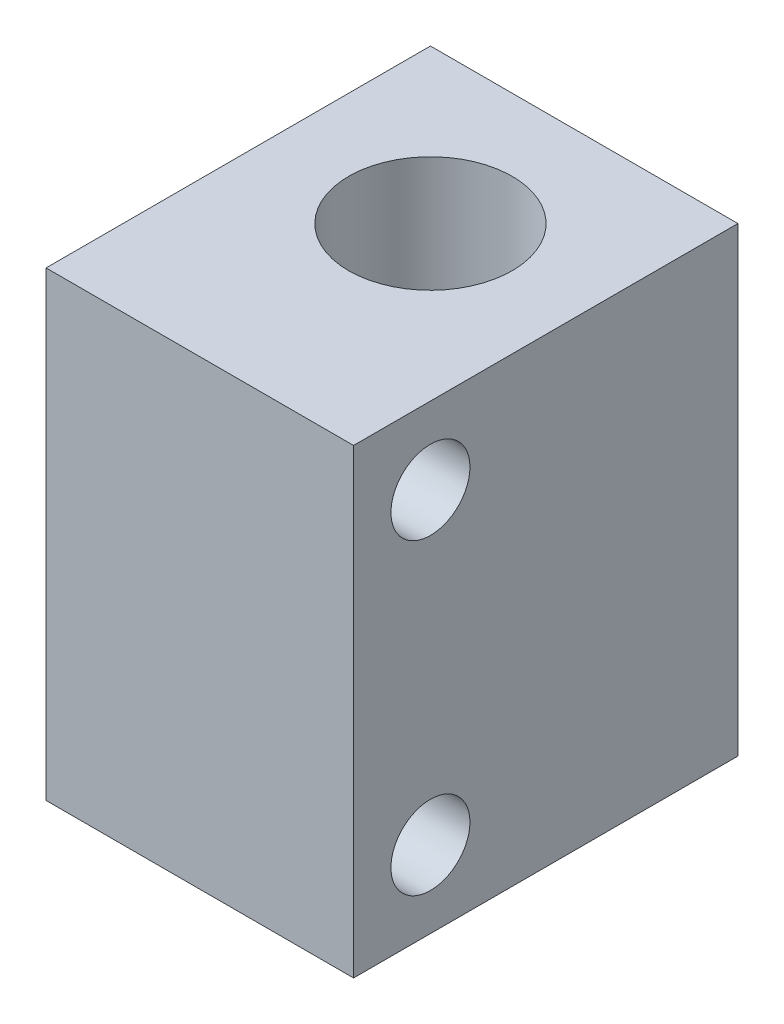
SolidWorks part; units mm, degrees
ref_plane "Front Plane" through (0, 0, 0) normal (0, 0, 1) x (1, 0, 0)
ref_plane "Top Plane" through (0, 0, 0) normal (0, 1, 0) x (1, 0, 0)
ref_plane "Right Plane" through (0, 0, 0) normal (1, 0, 0) x (0, 0, -1)
sketch "Sketch1" plane through (0, 0, 0) normal (0, 0, 1) x (1, 0, 0)
  line L1 (-6.35, -9.525) -> (6.35, -9.525)
  line L2 (-6.35, -9.525) -> (-6.35, 9.525)
  line L3 (-6.35, 9.525) -> (6.35, 9.525)
  line L4 (6.35, -9.525) -> (6.35, 9.525)
  line L5 (-6.35, -9.525) -> (6.35, 9.525) construction
  line L6 (-6.35, 9.525) -> (6.35, -9.525) construction
  point P0 (0, 0)
  dimension "D1" = 12.7
  dimension "D2" = 19.05
extrude "Boss-Extrude1" add sketch "Sketch1" along normal blind 15.875
sketch "Sketch3" plane through (0, 9.525, 0) normal (0, 1, 0) x (1, 0, 0)
  line L0 (0, 0) -> (0, -6.35) construction
  dimension "D1" = 6.35
hole_wizard "1/4 Clearance Hole1" positions "Sketch5" profile "Sketch4" hole size "1/4" standard "ANSI Inch" end condition through all
sketch "Sketch5" plane through (0, 9.525, 0) normal (0, 1, 0) x (1, 0, 0)
  point P0 (0, -6.35)
sketch "Sketch4" plane through (0, 9.525, 6.35) normal (1, 0, 0) x (0, 0, 1)
  line L0 (0, 0) -> (0, 19.05)
  line L1 (0, 19.05) -> (3.3782, 19.05)
  line L2 (3.3782, 19.05) -> (3.3782, 0)
  line L5 (3.3782, 0) -> (0, 0)
  line L11 (0, -6.35) -> (0, 107.95) construction
  dimension "Thru Hole Dia." = 6.7564
  dimension "Thru Hole Depth" = 19.05
sketch "Sketch9" plane through (6.35, 0, 0) normal (1, 0, 0) x (0, 0, -1)
  line L0 (0, 0) -> (-12.7, 0) construction
  line L1 (-12.7, 0) -> (-12.7, 6.35) construction
  line L2 (-12.7, 0) -> (-12.7, -6.35) construction
  dimension "D1" = 12.7
  dimension "D2" = 6.35
hole_wizard "#4 Clearance Hole1" positions "Sketch11" profile "Sketch10" hole size "#4" standard "ANSI Inch" end condition through all
sketch "Sketch11" plane through (6.35, 0, 0) normal (1, 0, 0) x (0, 0, -1)
  point P10 (-12.7, 6.35)
  point P13 (-12.7, -6.35)
sketch "Sketch10" plane through (6.35, 6.35, 12.7) normal (0, 1, 0) x (0, 0, -1)
  line L0 (0, 0) -> (0, 12.7)
  line L1 (0, 12.7) -> (1.6319, 12.7)
  line L2 (1.6319, 12.7) -> (1.6319, 0)
  line L5 (1.6319, 0) -> (0, 0)
  line L11 (0, -6.35) -> (0, 107.95) construction
  dimension "Thru Hole Dia." = 3.2639
  dimension "Thru Hole Depth" = 12.7
